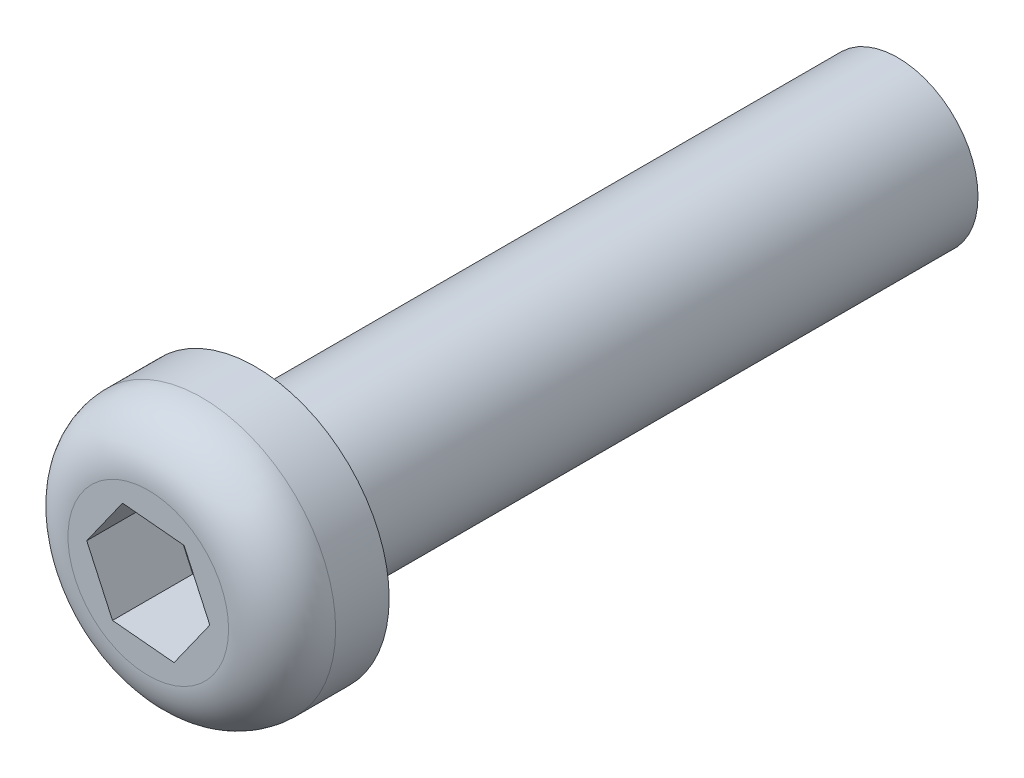
SolidWorks part; units mm, degrees
ref_plane "前视基准面" through (0, 0, 0) normal (0, 0, 1) x (1, 0, 0)
ref_plane "上视基准面" through (0, 0, 0) normal (0, 1, 0) x (1, 0, 0)
ref_plane "右视基准面" through (0, 0, 0) normal (1, 0, 0) x (0, 0, -1)
sketch "草图1" plane through (0, 0, 0) normal (0, 0, 1) x (1, 0, 0)
  circle A0 centre (0, 0) radius 1.5
  dimension "D1" = 3
extrude "凸台-拉伸1" add sketch "草图1" along normal blind 12
sketch "草图2" plane through (0, 0, 12) normal (0, 0, 1) x (1, 0, 0)
  circle A0 centre (0, 0) radius 2.5
  dimension "D1" = 5
extrude "凸台-拉伸2" add sketch "草图2" along normal blind 2
sketch "草图3" plane through (0, 0, 14) normal (0, 0, 1) x (1, 0, 0)
  line L1 (1.1496, -0.108) -> (0.6683, 0.9416)
  line L2 (0.6683, 0.9416) -> (-0.4813, 1.0496)
  line L3 (-0.4813, 1.0496) -> (-1.1496, 0.108)
  line L4 (-1.1496, 0.108) -> (-0.6683, -0.9416)
  line L5 (-0.6683, -0.9416) -> (0.4813, -1.0496)
  line L6 (0.4813, -1.0496) -> (1.1496, -0.108)
  circle A0 centre (0, 0) radius 1 construction
  dimension "D1" = 2
extrude "切除-拉伸1" cut sketch "草图3" against normal blind 1.5
fillet "圆角2" radius 1 1 edges at (2.5, 0, 14)
